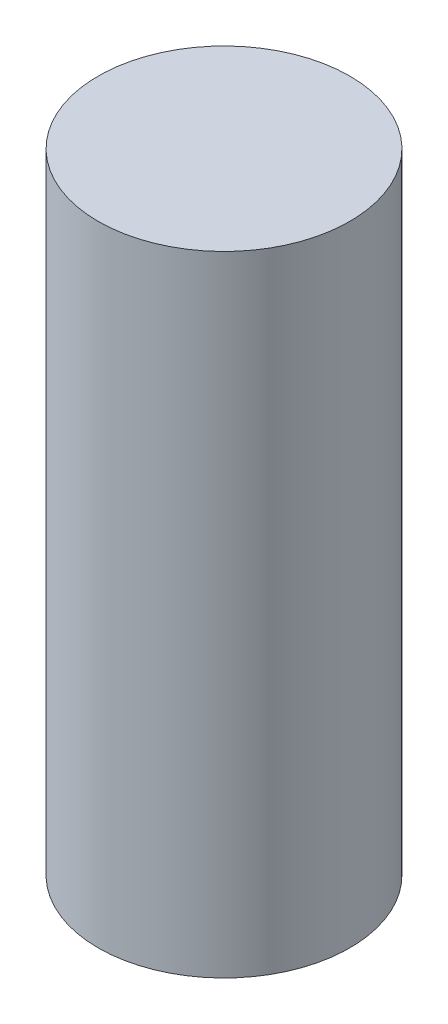
SolidWorks part; units mm, degrees
material "6061 合金"
ref_plane "前视基准面" through (0, 0, 0) normal (0, 0, 1) x (1, 0, 0)
ref_plane "上视基准面" through (0, 0, 0) normal (0, 1, 0) x (1, 0, 0)
ref_plane "右视基准面" through (0, 0, 0) normal (1, 0, 0) x (0, 0, -1)
sketch "草图1" plane through (0, 0, 0) normal (0, 1, 0) x (1, 0, 0)
  circle A0 centre (0, 0) radius 2
extrude "凸台-拉伸1" add sketch "草图1" along normal blind 10
